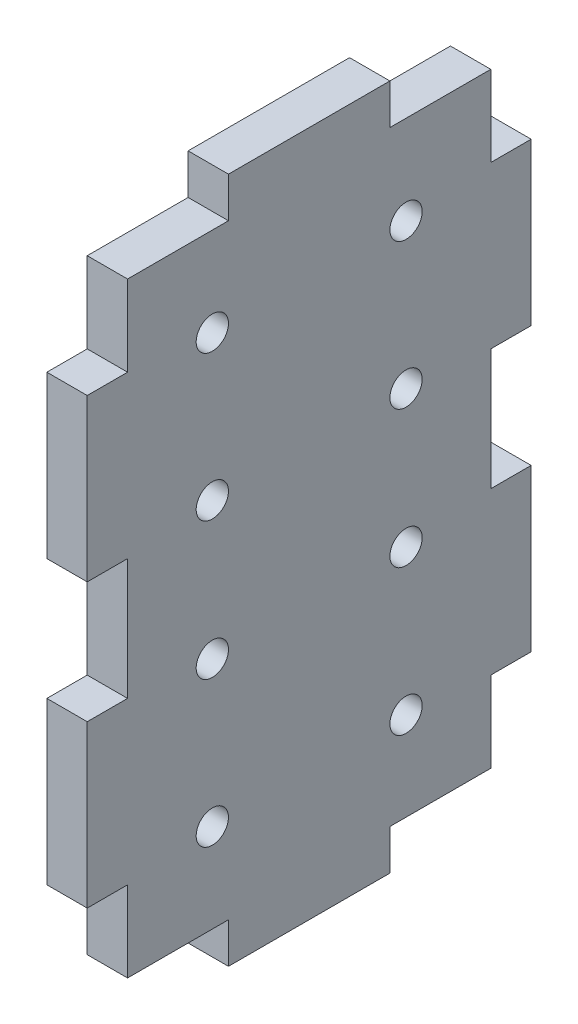
SolidWorks part; units mm, degrees
ref_plane "前视基准面" through (0, 0, 0) normal (0, 0, 1) x (1, 0, 0)
ref_plane "上视基准面" through (0, 0, 0) normal (0, 1, 0) x (1, 0, 0)
ref_plane "右视基准面" through (0, 0, 0) normal (1, 0, 0) x (0, 0, -1)
sketch "草图1" plane through (0, 0, 0) normal (1, 0, 0) x (0, 0, -1)
  line L0 (-32.5, 75) -> (-45, 75)
  line L1 (0, 0) -> (-12.5, 0)
  line L2 (0, 0) -> (0, 10)
  line L3 (0, 75) -> (-12.5, 75)
  line L4 (-45, 0) -> (-45, 10)
  line L5 (-22.5, 110.9943) -> (-22.5, -50.8387) construction
  line L6 (-32.5, 0) -> (-32.5, -5)
  line L7 (-32.5, -5) -> (-12.5, -5)
  line L8 (-12.5, 0) -> (-12.5, -5)
  line L9 (0, 10) -> (5, 10)
  line L11 (0, 30) -> (5, 30)
  line L12 (5, 10) -> (5, 30)
  line L13 (0, 45) -> (5, 45)
  line L15 (0, 65) -> (5, 65)
  line L16 (5, 45) -> (5, 65)
  line L18 (-12.5, 75) -> (-12.5, 80)
  line L19 (-12.5, 80) -> (-32.5, 80)
  line L20 (-32.5, 75) -> (-32.5, 80)
  line L21 (-45, 65) -> (-50, 65)
  line L23 (-45, 45) -> (-50, 45)
  line L24 (-50, 65) -> (-50, 45)
  line L25 (-45, 30) -> (-50, 30)
  line L27 (-45, 10) -> (-50, 10)
  line L28 (-50, 30) -> (-50, 10)
  line L29 (-45, 65) -> (-45, 75)
  line L30 (0, 65) -> (0, 75)
  line L31 (0, 30) -> (0, 45)
  line L32 (-45, 30) -> (-45, 45)
  line L33 (-32.5, 0) -> (-45, 0)
  circle A0 centre (-34.5, 64) radius 2
  circle A1 centre (-10.5, 64) radius 2
  circle A2 centre (-34.5, 46) radius 2
  circle A3 centre (-10.5, 46) radius 2
  circle A4 centre (-34.5, 11) radius 2
  circle A5 centre (-10.5, 11) radius 2
  circle A6 centre (-10.5, 29) radius 2
  circle A7 centre (-34.5, 29) radius 2
  dimension "D21" = 4
  dimension "D31" = 4
  dimension "D1" = 45
  dimension "D2" = 75
  dimension "D3" = 5
  dimension "D4" = 5
  dimension "D5" = 5
  dimension "D6" = 5
  dimension "D7" = 5
  dimension "D8" = 20
  dimension "D9" = 20
  dimension "D10" = 20
  dimension "D11" = 20
  dimension "D12" = 20
  dimension "D13" = 20
  dimension "D14" = 10
  dimension "D15" = 10
  dimension "D16" = 10
  dimension "D17" = 10
  dimension "D18" = 12.5
  dimension "D19" = 12.5
  dimension "D20" = 5
  dimension "D23" = 2
  dimension "D24" = 22.5
  dimension "D25" = 12
  dimension "D26" = 11
  dimension "D27" = 11
  dimension "D28" = 12
  dimension "D22" = 2
  dimension "D30" = 2
  dimension "D29" = 2
extrude "凸台-拉伸1" add sketch "草图1" along normal blind 5
